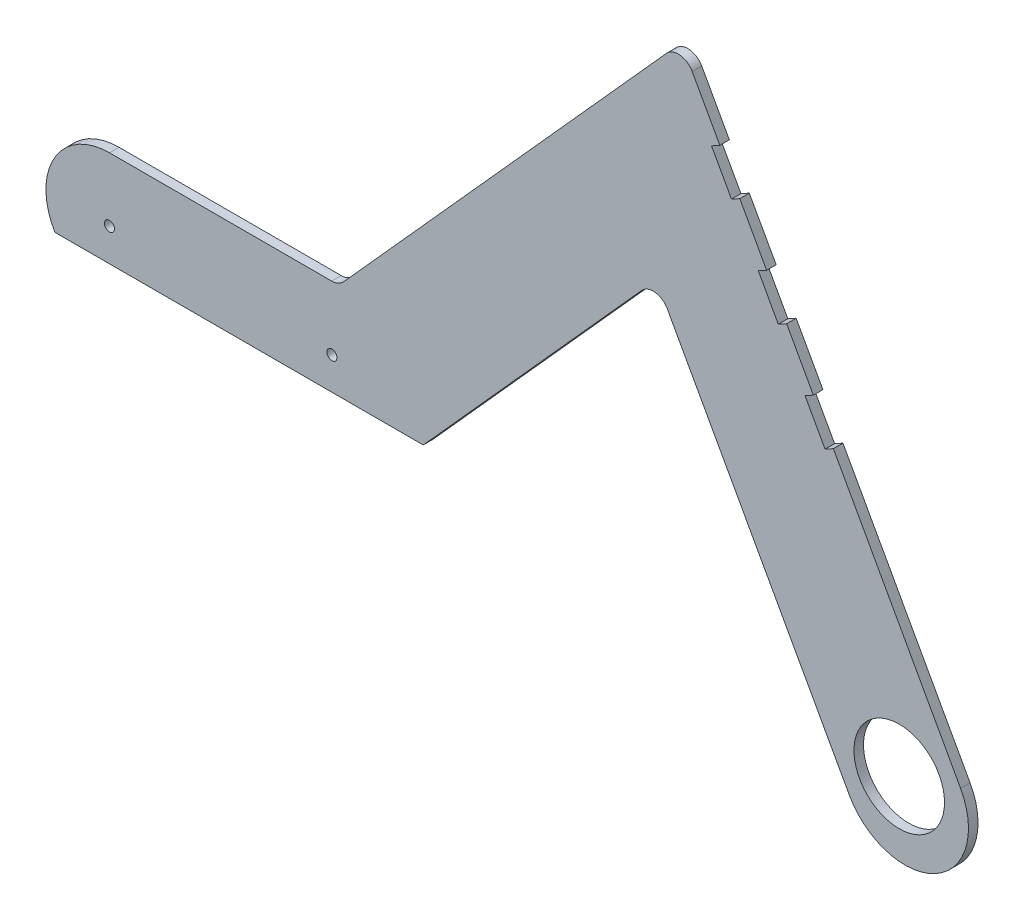
SolidWorks part; units mm, degrees
ref_plane "Front Plane" through (0, 0, 0) normal (0, 0, 1) x (1, 0, 0)
ref_plane "Top Plane" through (0, 0, 0) normal (0, 1, 0) x (1, 0, 0)
ref_plane "Right Plane" through (0, 0, 0) normal (1, 0, 0) x (0, 0, -1)
sketch "Croquis1" plane through (0, 0, 0) normal (0, 0, 1) x (1, 0, 0)
  line L0 (-135.8112, 31.6609) -> (-65.8732, 31.6609)
  line L1 (-62.1542, 33.3189) -> (39.488, 146.4297)
  line L2 (47.5853, 145.5024) -> (132.0431, -7.6343)
  line L3 (97.017, -26.9519) -> (39.7313, 76.9171)
  line L4 (31.634, 77.8443) -> (-44.3213, -6.6811)
  line L5 (-48.0403, -8.3391) -> (-135.8112, -8.3391)
  arc A0 (132.0431, -7.6343) -> (97.017, -26.9519) centre (114.53, -17.2931) cw
  arc A1 (-135.8112, -8.3391) -> (-135.8112, 31.6609) centre (-135.8112, 11.6609) cw
  circle A3 centre (-135.8112, 11.6609) radius 1.58
  circle A4 centre (-65.8112, 11.5885) radius 1.58
  circle A6 centre (112.7386, -14.0449) radius 14.25
  arc A7 (-62.1542, 33.3189) -> (-65.8732, 31.6609) centre (-65.8732, 36.6609) cw
  arc A8 (47.5853, 145.5024) -> (39.488, 146.4297) centre (43.2071, 143.0877) ccw
  arc A9 (39.7313, 76.9171) -> (31.634, 77.8443) centre (35.353, 74.5024) ccw
  arc A10 (-44.3213, -6.6811) -> (-48.0403, -8.3391) centre (-48.0403, -3.3391) cw
  point P17 (-155.8112, 11.6609)
  point P18 (124.1888, -34.8061)
  point P22 (44.1888, 151.6609)
  point P27 (-45.8112, -8.3391)
  dimension "D10" = 3.16
  dimension "D11" = 28.5
  dimension "D13" = 5
  dimension "D1" = 40
  dimension "D2" = 40
  dimension "D3" = 40
  dimension "D4" = 70
  dimension "D5" = 90
  dimension "D6" = 280
  dimension "D7" = 46.467
  dimension "D8" = 90
  dimension "D9" = 120
  dimension "D12" = 20
extrude "Saliente-Extruir1" add sketch "Croquis1" along normal blind 3
sketch "Croquis3" plane through (98.0182, 54.0589, 0) normal (0.8757, 0.4829, 0) x (0, 0, -1)
  line L0 (-3, -70.4538) -> (-3, 104.4289) construction
  line L1 (-3, 86.4289) -> (0, 86.4289)
  line L2 (-3, 86.4289) -> (-3, 73.4264)
  line L3 (-3, 73.4264) -> (0, 73.4264)
  line L4 (0, 86.4289) -> (0, 73.4264)
  line L5 (0, 86.4289) -> (-3, 86.4289) construction
  line L6 (0, -70.4538) -> (0, 104.4289) construction
  line L7 (0, 55.953) -> (-3, 55.953) construction
  line L8 (-3, 55.953) -> (0, 55.953)
  line L9 (-3, 55.953) -> (-3, 42.9048)
  line L10 (-3, 42.9048) -> (0, 42.9048)
  line L11 (0, 55.953) -> (0, 42.9048)
  line L12 (0, 42.9048) -> (-3, 42.9048) construction
  line L13 (0, 25.4771) -> (-3, 25.4771) construction
  line L14 (-3, 25.4771) -> (0, 25.4771)
  line L15 (-3, 25.4771) -> (-3, 12.4289)
  line L16 (-3, 12.4289) -> (0, 12.4289)
  line L17 (0, 25.4771) -> (0, 12.4289)
  line L18 (0, 12.4289) -> (-3, 12.4289) construction
extrude "Cortar-Extruir1" cut sketch "Croquis3" against normal blind 3
sketch "Croquis4" plane through (0, 0, 3) normal (0, 0, 1) x (1, 0, 0)
  line L1 (-30.3553, -8.6057) -> (-174.5944, -8.6057)
  line L2 (-30.3553, -8.6057) -> (-30.3553, 1.3943)
  line L3 (-30.3553, 1.3943) -> (-174.5944, 1.3943)
  line L4 (-174.5944, -8.6057) -> (-174.5944, 1.3943)
  point P4 (-30.3553, -8.6057)
  dimension "D1" = 10
extrude "Cortar-Extruir2" cut sketch "Croquis4" against normal blind 10
